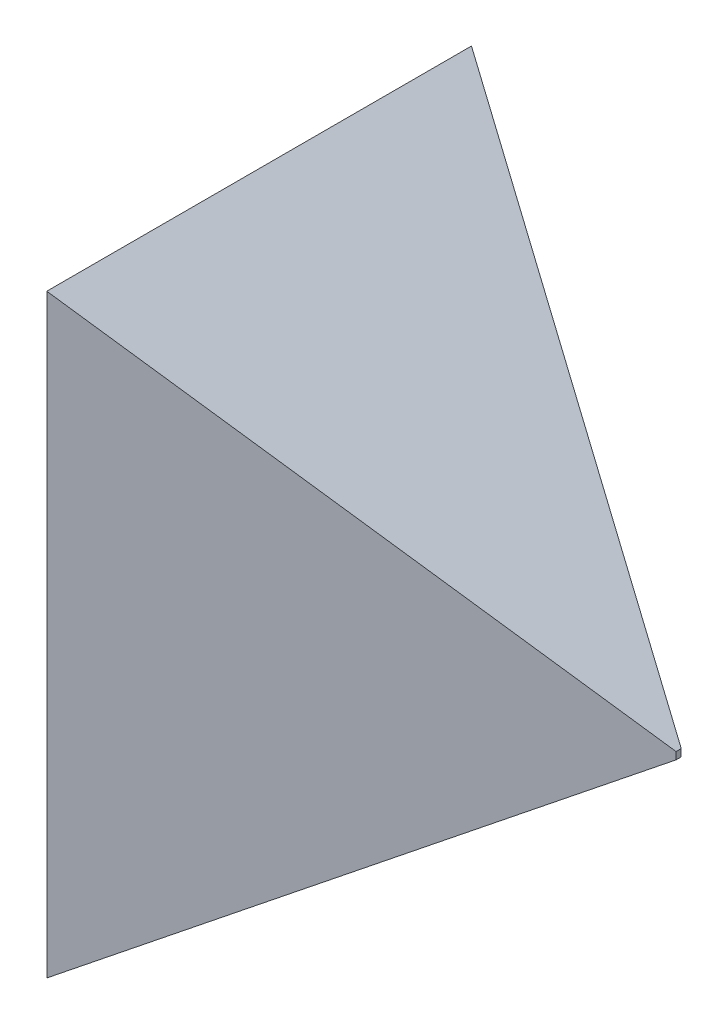
SolidWorks part; units mm, degrees
ref_plane "Front Plane" through (0, 0, 0) normal (0, 0, 1) x (1, 0, 0)
ref_plane "Top Plane" through (0, 0, 0) normal (0, 1, 0) x (1, 0, 0)
ref_plane "Right Plane" through (0, 0, 0) normal (1, 0, 0) x (0, 0, -1)
sketch "Sketch3" plane through (0, 0, 0) normal (0, 0, 1) x (1, 0, 0)
  line L0 (0, 0) -> (-16383.0409, 11471.5287)
  line L2 (0, 0) -> (-16383.0409, -11471.5287)
  arc A0 (-16383.0409, 11471.5287) -> (-16383.0409, -11471.5287) centre (0, 0) ccw
  dimension "D1" = 20000
  dimension "D2" = 70
extrude "Boss-Extrude1" add sketch "Sketch3" along normal blind 20000
sketch "Sketch20" plane through (0, 0, 0) normal (0, 1, 0) x (1, 0, 0)
  line L12 (0, -10000) -> (-20000, -20000)
  line L13 (0, -20000) -> (0, 0) construction
  line L14 (-20000, -20000) -> (0, -20000)
  line L15 (0, -20000) -> (0, -10000)
extrude "Cut-Extrude1" cut sketch "Sketch20" against normal through all both and the other way through all
sketch "Sketch22" plane through (0, 0, 0) normal (0, 1, 0) x (1, 0, 0)
  line L0 (0, -10000) -> (-20000, 0)
  line L1 (-20000, 0) -> (0, 0)
  line L2 (0, 0) -> (0, -10000)
extrude "Cut-Extrude2" cut sketch "Sketch22" against normal through all both and the other way through all
sketch "Sketch23" plane through (0, 0, 0) normal (0, 1, 0) x (1, 0, 0)
  line L0 (-200, -10100) -> (-200, -9900)
  line L1 (-16383.0409, -18191.5204) -> (0, -10000) construction
  line L2 (0, -10000) -> (-16383.0409, -1808.4796) construction
  line L3 (-200, -9900) -> (0, -10000)
  line L4 (0, -10000) -> (-200, -10100)
  dimension "D1" = 200
extrude "Cut-Extrude3" cut sketch "Sketch23" against normal through all both and the other way through all
sketch "Sketch24" plane through (0, 0, 0) normal (0, 1, 0) x (1, 0, 0)
  line L0 (-16383.0409, -18191.5204) -> (-16383.0409, -1808.4796)
  line L1 (-16383.0409, -1808.4796) -> (-20000, 0)
  line L2 (-20000, 0) -> (-20000, -20000)
  line L3 (-20000, -20000) -> (-16383.0409, -18191.5204)
extrude "Cut-Extrude4" cut sketch "Sketch24" against normal through all both and the other way through all
